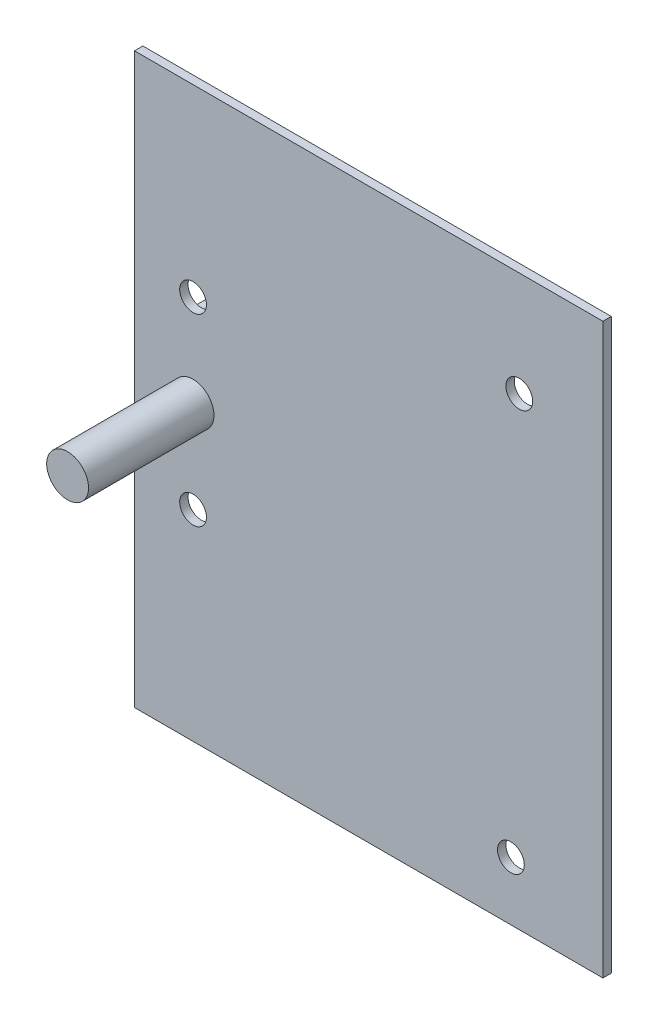
SolidWorks part; units mm, degrees
material "ﾕｰｻﾞｰ定義ﾌﾟﾗｽﾁｯｸ"
ref_plane "正面" through (0, 0, 0) normal (0, 0, 1) x (1, 0, 0)
ref_plane "平面" through (0, 0, 0) normal (0, 1, 0) x (1, 0, 0)
ref_plane "右側面" through (0, 0, 0) normal (1, 0, 0) x (0, 0, -1)
sketch "ｽｹｯﾁ1" plane through (0, 0, 0) normal (0, 0, 1) x (1, 0, 0)
  line L1 (-23, 40) -> (33, 40)
  line L2 (-23, 40) -> (-23, -28)
  line L3 (-23, -28) -> (33, -28)
  line L4 (33, 40) -> (33, -28)
  dimension "D1" = 56
  dimension "D2" = 68
  dimension "D3" = 23
  dimension "D4" = 40
extrude "ﾎﾞｽ - 押し出し1" add sketch "ｽｹｯﾁ1" along normal mid plane 1
sketch "ｽｹｯﾁ2" plane through (0, 0, 0.5) normal (0, 0, 1) x (1, 0, 0)
  line L0 (-23, -28) -> (33, -28) construction
  line L1 (-23, 40) -> (-23, -28) construction
  circle A0 centre (-16, 7) radius 2.5
  dimension "D1" = 35
  dimension "D2" = 5
  dimension "D3" = 7
extrude "ﾎﾞｽ - 押し出し2" add sketch "ｽｹｯﾁ2" along normal blind 15
sketch "ｽｹｯﾁ3" plane through (0, 0, -0.5) normal (0, 0, -1) x (-1, 0, 0)
  line L0 (23, -28) -> (-33, -28) construction
  line L1 (15, 12) -> (21, 12)
  line L2 (15, 12) -> (15, 2)
  line L3 (15, 2) -> (21, 2)
  line L4 (21, 12) -> (21, 2)
  line L5 (23, 40) -> (23, -28) construction
  dimension "D1" = 6
  dimension "D2" = 10
  dimension "D3" = 30
  dimension "D4" = 2
extrude "ﾎﾞｽ - 押し出し3" add sketch "ｽｹｯﾁ3" along normal blind 10
sketch "ｽｹｯﾁ4" plane through (0, 0, -0.5) normal (0, 0, -1) x (-1, 0, 0)
  line L0 (23, 40) -> (23, -28) construction
  line L1 (23, -28) -> (-33, -28) construction
  circle A0 centre (16, -4) radius 1.6
  dimension "D1" = 3.2
  dimension "D2" = 7
  dimension "D3" = 24
extrude "ｶｯﾄ - 押し出し1" cut sketch "ｽｹｯﾁ4" against normal blind 10
sketch "ｽｹｯﾁ5" plane through (0, 0, 0.5) normal (0, 0, 1) x (1, 0, 0)
  line L0 (-23, 40) -> (-23, -28) construction
  circle A0 centre (-16, 18) radius 1.6
  circle A1 centre (-16, -4) radius 1.6 construction
  dimension "D1" = 3.2
  dimension "D3" = 22
  dimension "D2" = 7
extrude "ｶｯﾄ - 押し出し2" cut sketch "ｽｹｯﾁ5" against normal blind 10
sketch "ｽｹｯﾁ6" plane through (0, 0, 0.5) normal (0, 0, 1) x (1, 0, 0)
  circle A0 centre (23, 27.5) radius 1.6
  circle A1 centre (-16, 18) radius 1.6 construction
  dimension "D1" = 3.2
  dimension "D2" = 39
  dimension "D3" = 9.5
extrude "ｶｯﾄ - 押し出し3" cut sketch "ｽｹｯﾁ6" against normal blind 10
sketch "ｽｹｯﾁ7" plane through (0, 0, 0.5) normal (0, 0, 1) x (1, 0, 0)
  circle A0 centre (22, -21) radius 1.6
  circle A1 centre (-16, -4) radius 1.6 construction
  dimension "D1" = 3.2
  dimension "D2" = 38
  dimension "D3" = 17
extrude "ｶｯﾄ - 押し出し4" cut sketch "ｽｹｯﾁ7" against normal blind 10
